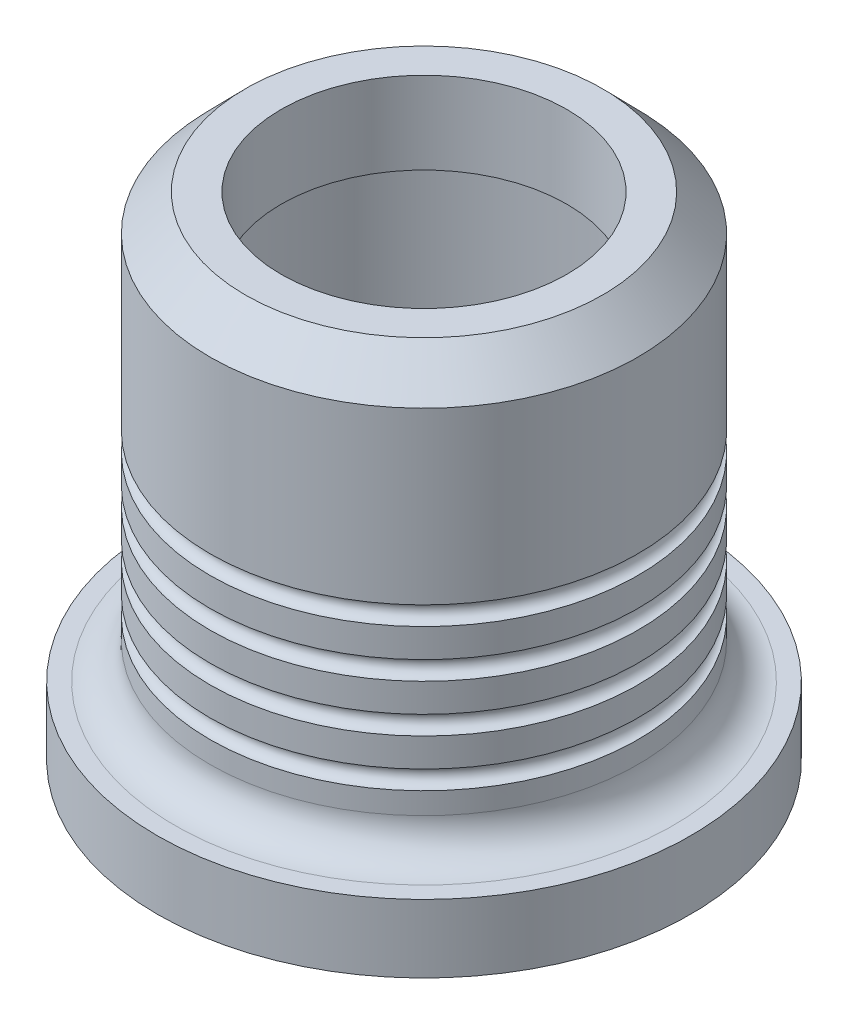
SolidWorks part; units mm, degrees
material "AISI 316 Annealed Stainless Steel Bar (SS)"
ref_plane "Front Plane" through (0, 0, 0) normal (0, 0, 1) x (1, 0, 0)
ref_plane "Top Plane" through (0, 0, 0) normal (0, 1, 0) x (1, 0, 0)
ref_plane "Right Plane" through (0, 0, 0) normal (1, 0, 0) x (0, 0, -1)
sketch "Sketch1" plane through (0, 0, 0) normal (0, 0, 1) x (1, 0, 0)
  line L0 (0, 28.0851) -> (0, -19.5571) construction
  line L2 (6.0918, 15.4309) -> (7.6159, 15.4309)
  line L3 (7.6159, 15.4309) -> (9.1225, 13.8931)
  line L4 (9.1225, 13.8931) -> (9.1225, 6.633)
  line L5 (9.1225, 5.833) -> (9.1225, 4.613)
  line L6 (9.1225, 3.813) -> (9.1225, 2.593)
  line L7 (9.1225, 1.793) -> (9.1225, 0.573)
  line L13 (9.1225, -0.227) -> (9.1225, -2.647)
  line L14 (9.1225, -2.647) -> (11.375, -2.647)
  line L15 (11.375, -2.647) -> (11.375, -5.547)
  line L17 (8.075, -5.547) -> (11.375, -5.547)
  line L18 (8.075, 11.9309) -> (6.0918, 11.9309)
  line L22 (8.075, -5.547) -> (8.075, -4.547)
  line L26 (8.075, -3.047) -> (8.075, 11.9309)
  line L27 (6.0918, 11.9309) -> (6.0918, 15.4309)
  arc A0 (9.1225, 6.633) -> (9.1225, 5.833) centre (9.1225, 6.233) ccw
  arc A1 (9.1225, 4.613) -> (9.1225, 3.813) centre (9.1225, 4.213) ccw
  arc A2 (9.1225, 2.593) -> (9.1225, 1.793) centre (9.1225, 2.193) ccw
  arc A3 (9.1225, 0.573) -> (9.1225, -0.227) centre (9.1225, 0.173) ccw
  arc A7 (8.075, -3.047) -> (8.075, -4.547) centre (7.1493, -3.797) cw
  point P36 (8.075, -2.047)
  dimension "D7" = 0.4
  dimension "D8" = 0.4
  dimension "D9" = 0.4
  dimension "D10" = 0.4
  dimension "D16" = 1.1914
  dimension "D2" = 3.5
  dimension "D3" = 1.5
  dimension "D4" = 1.22
  dimension "D5" = 1.22
  dimension "D6" = 1.22
  dimension "D11" = 2.42
  dimension "D12" = 2.9
  dimension "D13" = 16.15
  dimension "D14" = 1
  dimension "D15" = 3.3
  dimension "D17" = 1
  dimension "D18" = 1.0475
revolve "Revolve1" add sketch "Sketch1" angle 360 about L0
fillet "Fillet4" radius 1.5 1 edges at (0, -2.647, 9.1225)
